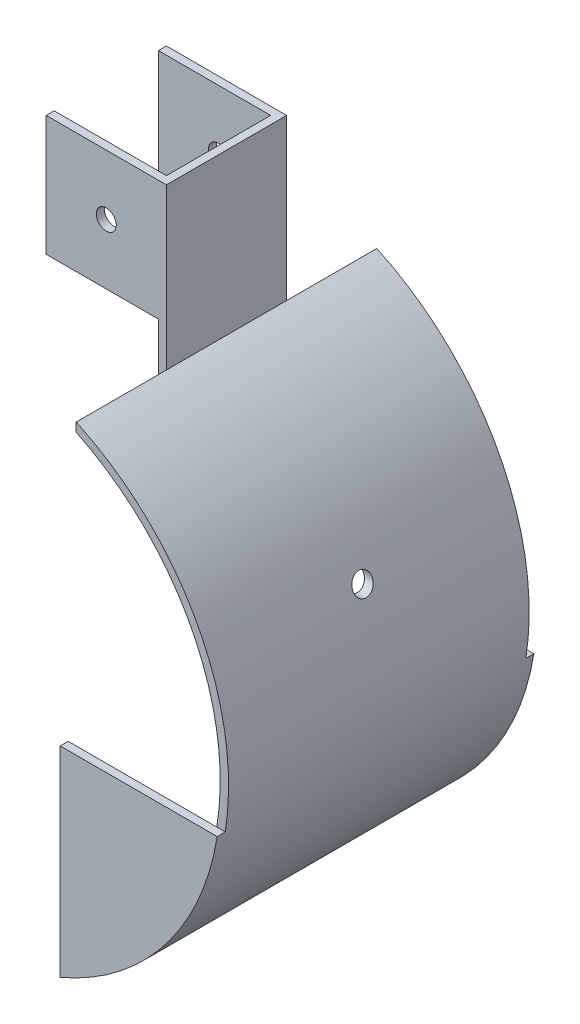
SolidWorks part; units mm, degrees
ref_plane "Front Plane" through (0, 0, 0) normal (0, 0, 1) x (1, 0, 0)
ref_plane "Top Plane" through (0, 0, 0) normal (0, 1, 0) x (1, 0, 0)
ref_plane "Right Plane" through (0, 0, 0) normal (1, 0, 0) x (0, 0, -1)
sketch "Sketch1" plane through (0, 0, 0) normal (0, 0, 1) x (1, 0, 0)
  line L0 (13, -144.9833) -> (12.135, -143.18)
  line L1 (-15, -15) -> (15, -15)
  line L2 (-15, -15) -> (-15, 15)
  line L3 (-15, 15) -> (15, 15)
  line L4 (15, -15) -> (15, 15)
  line L5 (-15, -15) -> (15, 15) construction
  line L6 (-15, 15) -> (15, -15) construction
  line L7 (15, -15) -> (13, -15)
  line L8 (15, -15) -> (15, -25)
  line L9 (15, -25) -> (13, -25)
  line L10 (13, -15) -> (13, -25)
  line L11 (13, -85.6418) -> (53, -85.6418)
  line L12 (13, -27) -> (13, -25)
  line L13 (14.1579, -26.8141) -> (13, -26.8141)
  line L14 (15, -25) -> (14.1579, -26.8141)
  line L15 (13, -26.8141) -> (13, -25)
  arc A0 (15, -25) -> (13, -144.9833) centre (-12.641, -84.5476) cw
  arc A1 (14.1579, -26.8141) -> (12.135, -143.18) centre (-12.7809, -84.5463) cw
  point P0 (0, 0)
  dimension "D1" = 30
  dimension "D2" = 30
  dimension "D3" = 10
  dimension "D4" = 2
  dimension "D5" = 120
  dimension "D6" = 40
  dimension "D7" = 2
  dimension "D8" = 2
  dimension "D9" = 2
extrude "Boss-Extrude1" add sketch "Sketch1" along normal blind 75 contours L1 L4 L3 L2 | L14 A1 L11 A0 | L1 L10 L9 L8 | L14 L9 L12 L13 | L11 A1 L0 A0
ref_plane "Plane1" through (0, 15, 0) normal (0, 1, 0) x (1, 0, 0)
sketch "Sketch2" plane through (0, 15, 0) normal (0, 1, 0) x (1, 0, 0)
  line L0 (-15, -37.5) -> (15, -37.5)
  line L1 (-15, -75) -> (-15, 0) construction
  line L2 (15, -75) -> (15, 0) construction
  line L3 (-15, -75) -> (15, -75) construction
  line L4 (-15, -52.5) -> (15, -52.5)
  line L5 (-15, -52.5) -> (-15, -22.5)
  line L6 (-15, -22.5) -> (15, -22.5)
  line L7 (15, -52.5) -> (15, -22.5)
  line L8 (-15, -52.5) -> (15, -22.5) construction
  line L9 (-15, -22.5) -> (15, -52.5) construction
  line L10 (-15, 0) -> (15, 0)
  line L11 (-15, 0) -> (-15, -22.5)
  line L12 (-15, -22.5) -> (15, -22.5)
  line L13 (15, 0) -> (15, -22.5)
  line L14 (-15, -52.5) -> (15, -52.5)
  line L15 (-15, -52.5) -> (-15, -75)
  line L16 (-15, -75) -> (15, -75)
  line L17 (15, -52.5) -> (15, -75)
  line L19 (-15, -52.5) -> (15, -52.5)
  line L20 (-15, -52.5) -> (-15, -75)
  line L21 (-15, -75) -> (15, -75)
  line L22 (15, -52.5) -> (15, -75)
  point P6 (0, -37.5)
  dimension "D1" = 30
extrude "Cut-Extrude1" cut sketch "Sketch2" against normal blind 75 contours L13 L10 L11 L6 | L17 L4 L15 L16
ref_plane "Plane2" through (-15, 0, 0) normal (-1, 0, 0) x (0, 0, 1)
sketch "Sketch3" plane through (-15, 0, 0) normal (-1, 0, 0) x (0, 0, 1)
  line L0 (37.5, -15) -> (37.5, 15.0607)
  line L1 (52.5, -15) -> (22.5, -15) construction
  line L2 (22.5, -15) -> (22.5, 15) construction
  line L3 (24.5, -15.0108) -> (50.5, -15.0108)
  line L4 (24.5, -15.0108) -> (24.5, 15.0714)
  line L5 (24.5, 15.0714) -> (50.5, 15.0714)
  line L6 (50.5, -15.0108) -> (50.5, 15.0714)
  line L7 (24.5, -15.0108) -> (50.5, 15.0714) construction
  line L8 (24.5, 15.0714) -> (50.5, -15.0108) construction
  point P4 (37.5, 0.0303)
  dimension "D1" = 2
extrude "Cut-Extrude2" cut sketch "Sketch3" against normal blind 28
sketch "Sketch4" plane through (0, 0, 52.5) normal (0, 0, 1) x (1, 0, 0)
  line L0 (-15, 0) -> (15, 0)
  line L1 (-15, -15) -> (-15, 15) construction
  line L2 (15, -25) -> (15, 15) construction
ref_plane "Plane3" through (0, 0, 52.5) normal (0, 0, 1) x (1, 0, 0)
sketch "Sketch5" plane through (0, 0, 52.5) normal (0, 0, 1) x (1, 0, 0)
  circle A0 centre (0, 0) radius 2.5
  dimension "D1" = 5
extrude "Cut-Extrude3" cut sketch "Sketch5" against normal blind 38
ref_plane "Plane4" through (0, 0, 75) normal (0, 0, 1) x (1, 0, 0)
sketch "Sketch6" plane through (0, 0, 75) normal (0, 0, 1) x (1, 0, 0)
  line L0 (13, -144.9833) -> (13, -94.9833)
  line L1 (13, -94.9833) -> (52.1744, -94.9833)
  arc A0 (13, -144.9833) -> (15, -25) centre (-12.641, -84.5476) ccw construction
  arc A1 (52.1744, -94.9833) -> (13, -144.9833) centre (-12.641, -84.5476) cw
  dimension "D1" = 50
extrude "Boss-Extrude2" add sketch "Sketch6" along normal blind 2
ref_plane "Plane5" through (0, 0, 0) normal (0, 0, -1) x (-1, 0, 0)
sketch "Sketch7" plane through (0, 0, 0) normal (0, 0, -1) x (-1, 0, 0)
  line L0 (-13, -144.9833) -> (-13, -94.9833)
  line L1 (-13, -94.9833) -> (-52.1744, -94.9833)
  arc A0 (-15, -25) -> (-13, -144.9833) centre (12.641, -84.5476) ccw construction
  arc A1 (-52.1744, -94.9833) -> (-13, -144.9833) centre (12.641, -84.5476) ccw
  dimension "D1" = 50
extrude "Boss-Extrude3" add sketch "Sketch7" along normal blind 2
ref_plane "Plane6" through (10.46, 0, 0) normal (-1, 0, 0) x (0, 0, 1)
sketch "Sketch9" plane through (13, 0, 0) normal (-1, 0, 0) x (0, 0, 1)
  line L0 (22.5, -26.8141) -> (52.5, -26.8141)
  line L1 (52.5, -26.8141) -> (22.5, -26.8141) construction
  line L2 (37.5, -26.8141) -> (37.5, -61.8141)
  circle A0 centre (37.5, -61.8141) radius 2.5
  dimension "D2" = 5
  dimension "D1" = 35
extrude "Cut-Extrude4" cut sketch "Sketch9" against normal through all
